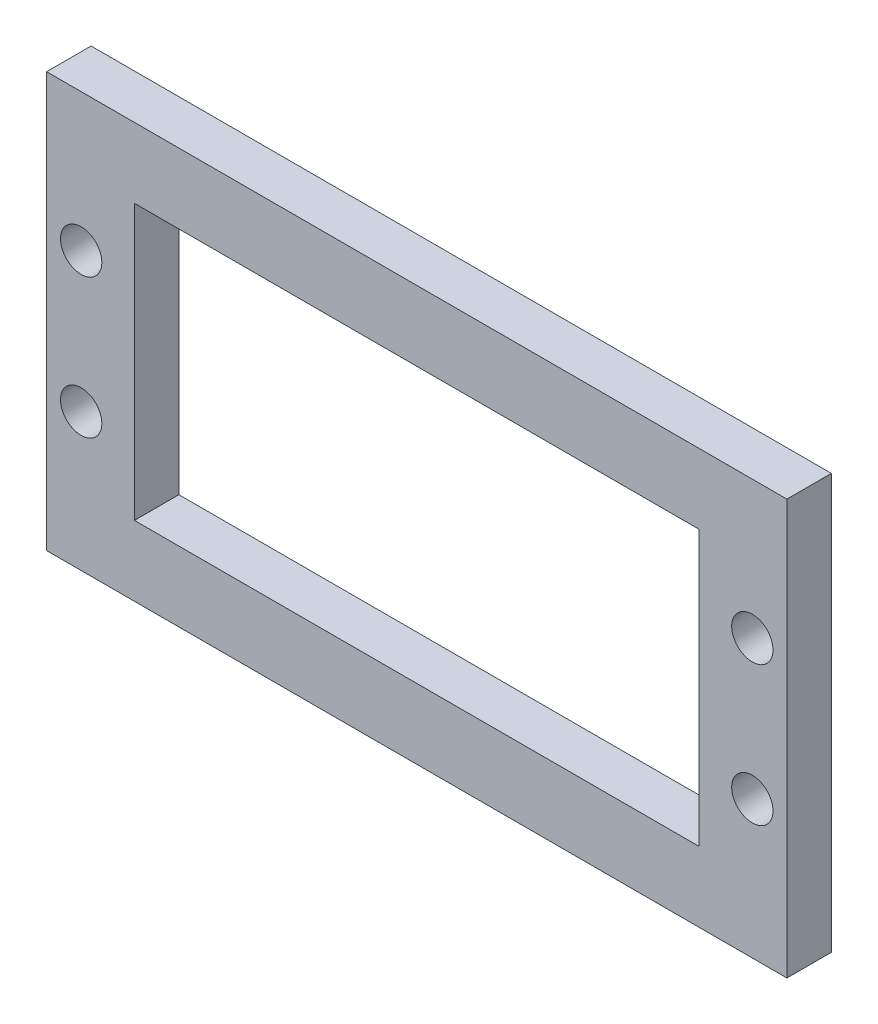
SolidWorks part; units mm, degrees
ref_plane "Front Plane" through (0, 0, 0) normal (0, 0, 1) x (1, 0, 0)
ref_plane "Top Plane" through (0, 0, 0) normal (0, 1, 0) x (1, 0, 0)
ref_plane "Right Plane" through (0, 0, 0) normal (1, 0, 0) x (0, 0, -1)
sketch "Sketch1" plane through (0, 0, 0) normal (0, 0, 1) x (1, 0, 0)
  line L1 (-26.416, -9.8) -> (26.416, -9.8)
  line L2 (-26.416, -9.8) -> (-26.416, 9.8)
  line L3 (-26.416, 9.8) -> (26.416, 9.8)
  line L4 (26.416, -9.8) -> (26.416, 9.8)
  line L5 (-26.416, -9.8) -> (26.416, 9.8) construction
  line L6 (-26.416, 9.8) -> (26.416, -9.8) construction
  line L7 (-20.15, -9.8) -> (20.15, -9.8)
  line L8 (-20.15, -9.8) -> (-20.15, 9.8)
  line L9 (-20.15, 9.8) -> (20.15, 9.8)
  line L10 (20.15, -9.8) -> (20.15, 9.8)
  line L11 (-20.15, -9.8) -> (20.15, 9.8) construction
  line L12 (-20.15, 9.8) -> (20.15, -9.8) construction
  line L13 (-26.416, 9.8) -> (26.416, 9.8)
  line L14 (-26.416, 9.8) -> (-26.416, 14.8)
  line L15 (-26.416, 14.8) -> (26.416, 14.8)
  line L16 (26.416, 9.8) -> (26.416, 14.8)
  line L17 (26.416, -9.8) -> (-26.416, -9.8)
  line L18 (26.416, -9.8) -> (26.416, -14.8)
  line L19 (26.416, -14.8) -> (-26.416, -14.8)
  line L20 (-26.416, -9.8) -> (-26.416, -14.8)
  circle A0 centre (-23.95, -4.974) radius 1.475
  circle A1 centre (-23.95, 4.974) radius 1.475
  circle A2 centre (23.95, 4.974) radius 1.475
  circle A3 centre (23.95, -4.974) radius 1.475
  point P0 (0, 0)
  point P14 (0, 0)
  dimension "D1" = 2.95
  dimension "D2" = 2.95
  dimension "D3" = 2.95
  dimension "D4" = 2.95
  dimension "D7" = 4.826
  dimension "D8" = 3.8
  dimension "D9" = 3.8
  dimension "D10" = 4.826
  dimension "D11" = 4.826
  dimension "D12" = 4.826
  dimension "D13" = 3.8
  dimension "D5" = 19.6
  dimension "D6" = 52.832
  dimension "D15" = 40.3
  dimension "D16" = 5
  dimension "D17" = 5
  dimension "3.9" = 3.8
extrude "Boss-Extrude2" add sketch "Sketch1" along normal blind 3.175 contours L1 L8 L3 L2 A1 A0 | L10 L1 L4 L3 A3 A2 | L14 L13 L16 L15 | L18 L17 L20 L19
